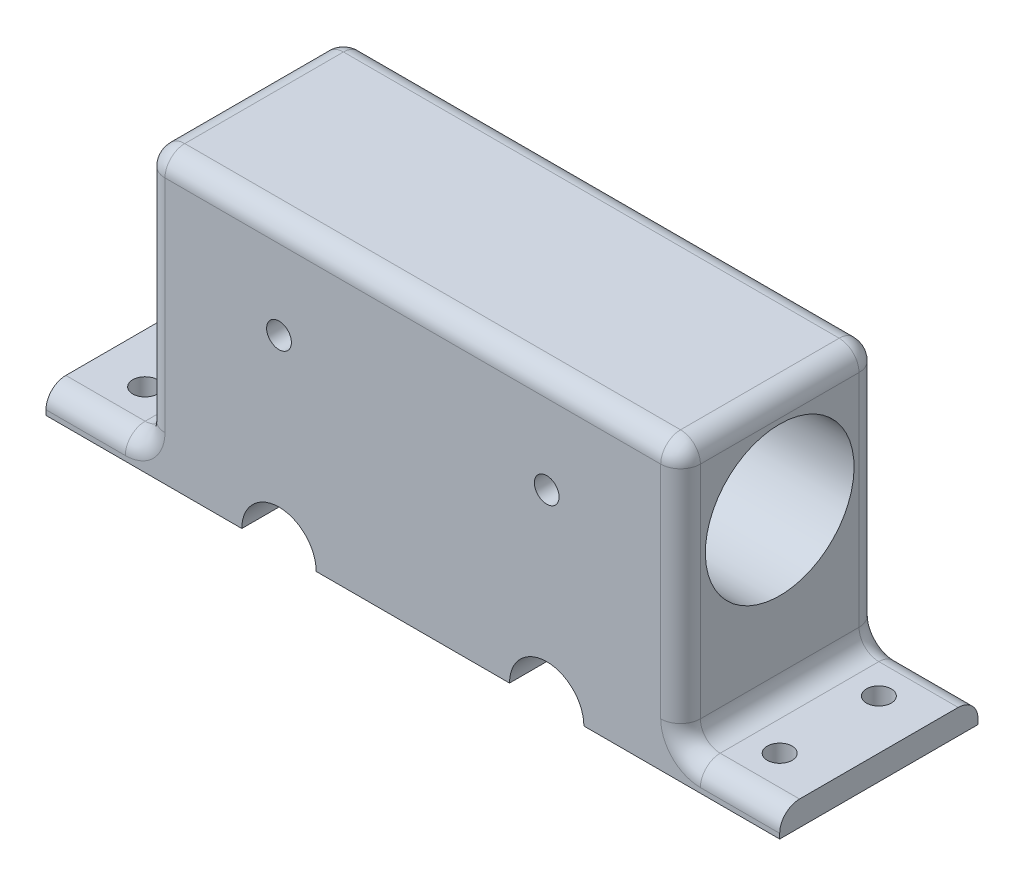
SolidWorks part; units mm, degrees
ref_plane "Front Plane" through (0, 0, 0) normal (0, 0, 1) x (1, 0, 0)
ref_plane "Top Plane" through (0, 0, 0) normal (0, 1, 0) x (1, 0, 0)
ref_plane "Right Plane" through (0, 0, 0) normal (1, 0, 0) x (0, 0, -1)
sketch "Sketch1" plane through (0, 0, 0) normal (0, 0, 1) x (1, 0, 0)
  line L6 (-12.3825, 0) -> (12.3825, 0)
  line L7 (12.3825, 0) -> (21.9075, 0) construction
  line L8 (21.9075, 0) -> (46.99, 0)
  line L9 (46.99, 0) -> (46.99, 3.175)
  line L10 (46.99, 3.175) -> (36.83, 3.175)
  line L11 (34.29, 5.715) -> (34.29, 36.5125)
  line L12 (34.29, 36.5125) -> (-34.29, 36.5125)
  line L13 (0, 36.5125) -> (0, 0) construction
  line L14 (-12.3825, 0) -> (-21.9075, 0) construction
  line L19 (-34.29, 5.715) -> (-34.29, 36.5125)
  line L20 (-46.99, 3.175) -> (-36.83, 3.175)
  line L21 (-46.99, 0) -> (-46.99, 3.175)
  line L22 (-21.9075, 0) -> (-46.99, 0)
  arc A0 (12.3825, 0) -> (21.9075, 0) centre (17.145, 0) cw
  arc A2 (36.83, 3.175) -> (34.29, 5.715) centre (36.83, 5.715) cw
  arc A3 (-36.83, 3.175) -> (-34.29, 5.715) centre (-36.83, 5.715) ccw
  arc A4 (-12.3825, 0) -> (-21.9075, 0) centre (-17.145, 0) ccw
  point P18 (34.29, 3.175)
  point P21 (-34.29, 3.175)
  dimension "D1" = 4.7625
  dimension "D7" = 2.54
  dimension "D2" = 17.145
  dimension "D4" = 12.7
  dimension "D5" = 3.175
  dimension "D6" = 33.3375
  dimension "D3" = 34.29
extrude "Boss-Extrude1" add sketch "Sketch1" along normal blind 25.4
sketch "Sketch2" plane through (0, 3.175, 0) normal (0, 1, 0) x (1, 0, 0)
  line L0 (40.64, -37.966) -> (40.64, 12.566) construction
  line L3 (40.64, -12.7) -> (34.29, -12.7) construction
  line L4 (0, 0) -> (0, -25.4) construction
  line L5 (34.29, -25.4) -> (-34.29, -25.4) construction
  line L7 (34.29, -25.4) -> (34.29, 0) construction
  circle A0 centre (40.64, -6.35) radius 1.5875
  circle A1 centre (40.64, -19.05) radius 1.5875
  circle A2 centre (-40.64, -6.35) radius 1.5875
  circle A3 centre (-40.64, -19.05) radius 1.5875
  dimension "D1" = 3.175
  dimension "D2" = 6.35
  dimension "D3" = 6.35
extrude "Cut-Extrude1" cut sketch "Sketch2" against normal through all
sketch "Sketch3" plane through (34.29, 0, 0) normal (1, 0, 0) x (0, 0, -1)
  line L0 (-12.7, 36.5125) -> (-12.7, 3.175) construction
  line L1 (-25.4, 36.5125) -> (0, 36.5125) construction
  line L2 (-25.4, 3.175) -> (0, 3.175) construction
  circle A0 centre (-12.7, 23.8125) radius 9.525
  dimension "D1" = 19.05
  dimension "D2" = 12.7
extrude "Cut-Extrude2" cut sketch "Sketch3" against normal through all
sketch "Sketch4" plane through (0, 0, 25.4) normal (0, 0, 1) x (1, 0, 0)
  line L0 (0, 0) -> (0, 36.5125) construction
  line L1 (-12.3825, 0) -> (12.3825, 0) construction
  line L2 (34.29, 36.5125) -> (-34.29, 36.5125) construction
  line L3 (17.145, 23.8125) -> (-17.145, 23.8125) construction
  circle A0 centre (17.145, 23.8125) radius 1.5875
  circle A1 centre (-17.145, 23.8125) radius 1.5875
  point P9 (0, 23.8125)
  dimension "D2" = 17.145
  dimension "D3" = 3.175
  dimension "D1" = 12.7
extrude "Cut-Extrude3" cut sketch "Sketch4" against normal through all
fillet "Fillet1" radius 2.54 16 edges at (41.91, 3.175, 0) (35.0339, 3.9189, 0) (41.91, 3.175, 25.4) (35.0339, 3.9189, 25.4) (34.29, 21.1137, 0) (34.29, 21.1137, 25.4) (-41.91, 3.175, 0) (-35.0339, 3.9189, 0) (-41.91, 3.175, 25.4) (-35.0339, 3.9189, 25.4) (0, 36.5125, 0) (0, 36.5125, 25.4) (-34.29, 36.5125, 12.7) (-34.29, 21.1137, 0) (-34.29, 21.1137, 25.4) (34.29, 36.5125, 12.7)
equation "\"span\"= 48"
equation "\"wing_chord\"= 9"
equation "\"fuse_len\"= 15"
equation "\"fuse_height\"= 5"
equation "\"fuse_wid\"= 5"
equation "\"foam_t\"= 0.1875"
equation "\"main_spar_len\"= 36"
equation "\"x_fuse_to_wing\"= 3"
equation "\"x_cg_from_le\"= 2.25"
equation "\"boom_len\"= 30"
equation "\"wing_spar_d\"= 0.375"
equation "\"wing_spar_spacing\"= 1.35"
equation "\"D1@Sketch1\"=\"wing_spar_d\"/2"
equation "\"D2@Sketch1\"=\"wing_spar_spacing\"/2"
equation "\"wing_spar_l\"= 48"
equation "\"wing_mount_l\"= 2.5"
equation "\"D1@Boss-Extrude1\"=\"boom_mount_l\""
equation "\"D2@Sketch2\"=\"boom_mount_l\"/4"
equation "\"boom_d\"= 0.75"
equation "\"D1@Sketch3\"=\"boom_d\""
equation "\"D2@Sketch3\"=\"boom_d\"/2 + .125"
equation "\"D6@Sketch1\"=\"boom_d\"*1.75"
equation "\"D1@Sketch4\"= \"boom_d\"/2 + 1/8"
equation "\"D2@Sketch4\"= \"wing_spar_spacing\"/2"
equation "\"D3@Sketch1\"= \"wing_spar_spacing\""
equation "\"wing_angle\"= 1.5"
equation "\"boom_mount_l\"= 1"
equation "\"vstab_span\"= 6.5"
equation "\"hstab_span\"= 15.25"
equation "\"tail_chord\"= 5"
